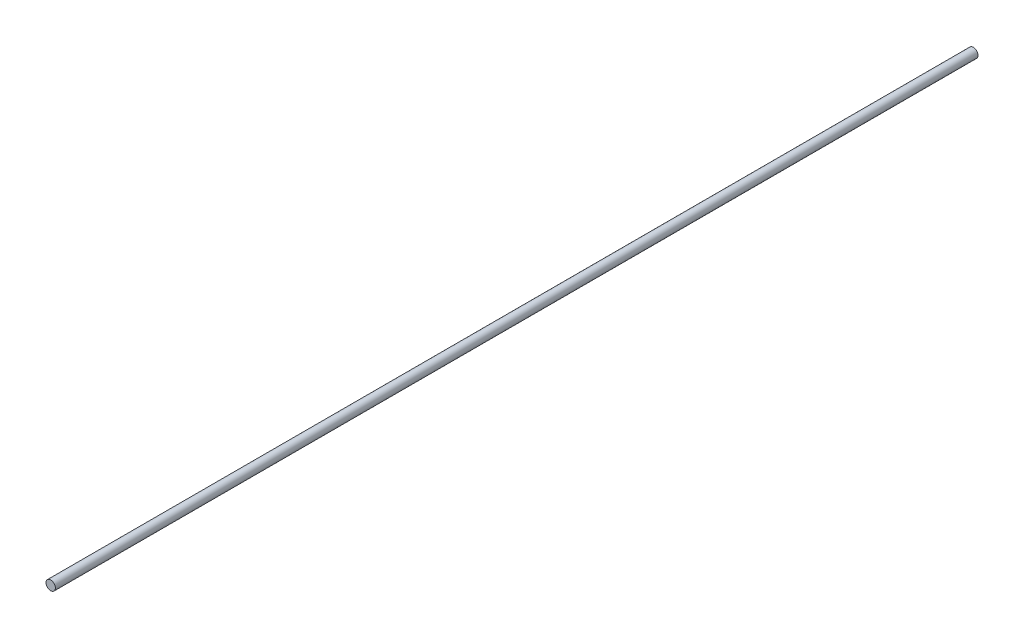
SolidWorks part; units mm, degrees
material "AISI 1020"
ref_plane "Front Plane" through (0, 0, 0) normal (0, 0, 1) x (1, 0, 0)
ref_plane "Top Plane" through (0, 0, 0) normal (0, 1, 0) x (1, 0, 0)
ref_plane "Right Plane" through (0, 0, 0) normal (1, 0, 0) x (0, 0, -1)
sketch "Sketch1" plane through (0, 0, 0) normal (0, 0, 1) x (1, 0, 0)
  circle A0 centre (0, 0) radius 7.9375
  dimension "D1" = 15.875
extrude "Boss-Extrude1" add sketch "Sketch1" along normal blind 2254.25
sketch "Sketch2" plane through (0, 0, 0) normal (0, 0, -1) x (-1, 0, 0)
  circle A0 centre (0, 0) radius 7.9375
extrude "Cut-Extrude1" cut sketch "Sketch2" against normal blind 438.15
sketch "Sketch3" plane through (0, 0, 2254.25) normal (0, 0, 1) x (1, 0, 0)
  circle A0 centre (0, 0) radius 7.9375
extrude "Cut-Extrude2" cut sketch "Sketch3" against normal blind 254
